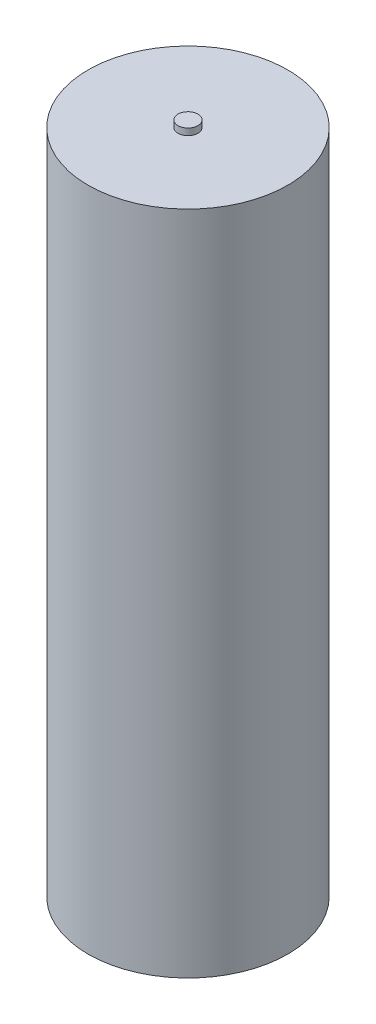
SolidWorks part; units mm, degrees
ref_plane "Front Plane" through (0, 0, 0) normal (0, 0, 1) x (1, 0, 0)
ref_plane "Top Plane" through (0, 0, 0) normal (0, 1, 0) x (1, 0, 0)
ref_plane "Right Plane" through (0, 0, 0) normal (1, 0, 0) x (0, 0, -1)
sketch "Sketch1" plane through (0, 0, 0) normal (0, 1, 0) x (1, 0, 0)
  circle A0 centre (0, 0) radius 1500
  dimension "D1" = 3000
extrude "Boss-Extrude1" add sketch "Sketch1" along normal blind 10000
sketch "Sketch2" plane through (0, 10000, 0) normal (0, 1, 0) x (1, 0, 0)
  circle A0 centre (0, 0) radius 150
extrude "Boss-Extrude2" add sketch "Sketch2" along normal blind 100
